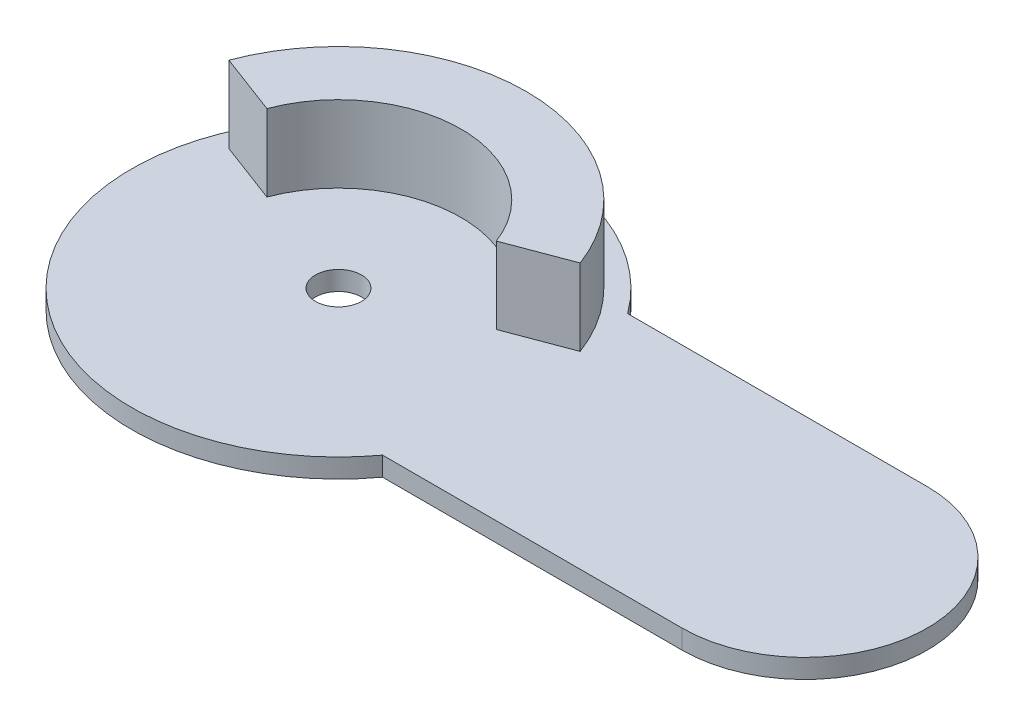
SolidWorks part; units mm, degrees
ref_plane "Front Plane" through (0, 0, 0) normal (0, 0, 1) x (1, 0, 0)
ref_plane "Top Plane" through (0, 0, 0) normal (0, 1, 0) x (1, 0, 0)
ref_plane "Right Plane" through (0, 0, 0) normal (1, 0, 0) x (0, 0, -1)
sketch "Sketch1" plane through (0, 0, 0) normal (0, 1, 0) x (1, 0, 0)
  line L0 (-6.875, 0) -> (6.875, 0) construction
  line L1 (-22.9311, 8.6264) -> (-17.0509, 24.2574) construction
  line L2 (-22.9311, 8.6264) -> (-14.9754, 5.6336)
  line L3 (0, -6.875) -> (0, 6.875) construction
  line L4 (22.9311, 8.6264) -> (14.9754, 5.6336)
  line L5 (-23.9844, 5) -> (23.9844, 5) construction
  circle A0 centre (0, 0) radius 16 construction
  circle A1 centre (0, 0) radius 24.5 construction
  arc A2 (-22.9311, 8.6264) -> (22.9311, 8.6264) centre (0, 0) cw
  arc A3 (-14.9754, 5.6336) -> (14.9754, 5.6336) centre (0, 0) cw
  point P20 (-18.9532, 7.13)
  dimension "D1" = 32
  dimension "D2" = 49
  dimension "D3" = 2.13
  dimension "D4" = 5
extrude "Boss-Extrude1" add sketch "Sketch1" along normal blind 10 contours A2 L4 A3 L2
sketch "Sketch2" plane through (0, 0, 0) normal (0, -1, 0) x (1, 0, 0)
  line L1 (76.8704, -16) -> (76.8704, 16)
  line L3 (21.7486, -16) -> (76.8704, -16)
  line L5 (21.7486, 16) -> (76.8704, 16)
  circle A1 centre (0, 0) radius 27 construction
  circle A2 centre (0, 0) radius 3
  arc A3 (0, -27) -> (0, 27) centre (0, 0) cw
  circle A4 centre (0, 0) radius 16 construction
  arc A5 (21.7486, -16) -> (0, -27) centre (0, 0) cw
  arc A6 (0, 27) -> (21.7486, 16) centre (0, 0) cw
  dimension "D1" = 54
  dimension "D2" = 6
extrude "Boss-Extrude2" add sketch "Sketch2" along normal blind 2.5
sketch "Sketch3" plane through (0, 0, 0) normal (0, 1, 0) x (1, 0, 0)
  line L0 (21.7486, 16) -> (76.8704, 16) construction
  line L1 (76.8704, -16) -> (21.7486, -16) construction
  line L2 (-6.875, 0) -> (6.875, 0) construction
  line L3 (76.8704, 16) -> (76.8704, -16) construction
  line L4 (60.8704, 16) -> (76.8704, 16)
  line L5 (76.8704, 16) -> (76.8704, -16)
  line L6 (76.8704, -16) -> (60.8704, -16)
  arc A0 (60.8704, 16) -> (60.8704, -16) centre (60.8704, 0) cw
  point P10 (76.8704, 0)
  line M2 (76.8704, 16) -> (21.7486, 16)
  line M4 (21.7486, -16) -> (76.8704, -16)
  line M5 (76.8704, -16) -> (76.8704, 16)
extrude "Cut-Extrude1" cut sketch "Sketch3" against normal blind 10 contours A0 L5 M2 | A0 M5 M4
